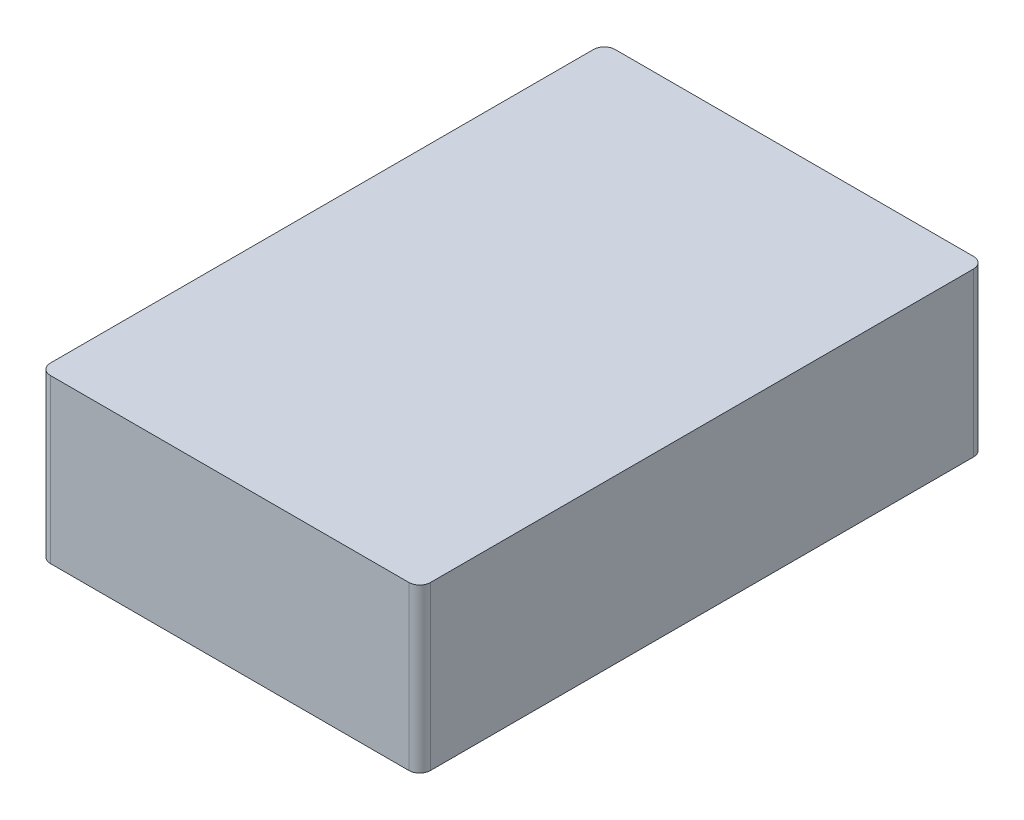
SolidWorks part; units mm, degrees
ref_plane "Front Plane" through (0, 0, 0) normal (0, 0, 1) x (1, 0, 0)
ref_plane "Top Plane" through (0, 0, 0) normal (0, 1, 0) x (1, 0, 0)
ref_plane "Right Plane" through (0, 0, 0) normal (1, 0, 0) x (0, 0, -1)
sketch "Sketch1" plane through (0, 0, 0) normal (0, 1, 0) x (1, 0, 0)
  line L1 (-17.5, 26) -> (17.5, 26)
  line L2 (-17.5, 26) -> (-17.5, -26)
  line L3 (-17.5, -26) -> (17.5, -26)
  line L4 (17.5, 26) -> (17.5, -26)
  line L5 (-17.5, 26) -> (17.5, -26) construction
  line L6 (-17.5, -26) -> (17.5, 26) construction
  point P0 (0, 0)
  dimension "D1" = 52
  dimension "D2" = 35
extrude "Boss-Extrude1" add sketch "Sketch1" along normal blind 15
fillet "Fillet1" radius 1 4 edges at (-17.5, 7.5, -26) (17.5, 7.5, -26) (17.5, 7.5, 26) (-17.5, 7.5, 26)
